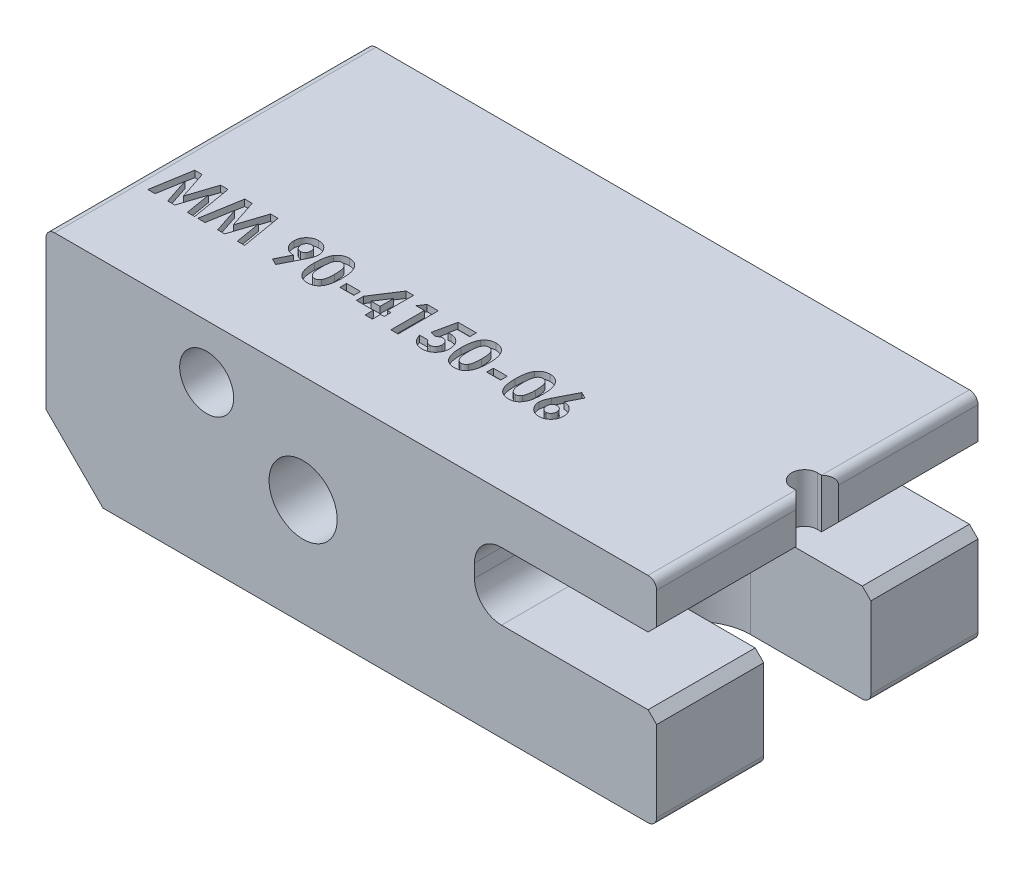
SolidWorks part; units mm, degrees
material "Acero M2"
ref_plane "Alzado" through (0, 0, 0) normal (0, 0, 1) x (1, 0, 0)
ref_plane "Planta" through (0, 0, 0) normal (0, 1, 0) x (1, 0, 0)
ref_plane "Vista lateral" through (0, 0, 0) normal (1, 0, 0) x (0, 0, -1)
sketch "Croquis1" plane through (0, 0, 0) normal (0, 1, 0) x (1, 0, 0)
  line L1 (0, 0) -> (36.195, 0)
  line L2 (0, 0) -> (0, -19.05)
  line L3 (0, -19.05) -> (36.195, -19.05)
  line L4 (36.195, 0) -> (36.195, -19.05)
  line L5 (18.0975, -19.05) -> (18.0975, 0) construction
  line L6 (0, -9.525) -> (36.195, -9.525) construction
  point P88 (18.0975, -9.525)
  dimension "D1" = 19.05
  dimension "D2" = 36.195
extrude "Saliente-Extruir1" add sketch "Croquis1" along normal blind 12.7
hole_wizard "Taladro roscado #10-321" positions "Croquis2" profile "Croquis3" tap size "#10-32" standard "Ansi Inch" end condition up to next
sketch "Croquis2" plane through (0, 0, 19.05) normal (0, 0, 1) x (1, 0, 0)
  line L0 (0, 12.7) -> (0, 0) construction
  line L1 (0, 12.7) -> (36.195, 12.7) construction
  point P0 (15.24, 6.35)
  dimension "D1" = 15.24
  dimension "D2" = 6.35
sketch "Croquis3" plane through (15.24, 6.35, 19.05) normal (1, 0, 0) x (0, -1, 0)
  line L0 (0, 0) -> (0, 19.05)
  line L1 (0, 19.05) -> (2.0193, 19.05)
  line L2 (2.0193, 19.05) -> (2.0193, 0)
  line L5 (2.0193, 0) -> (0, 0)
  line L11 (0, -6.35) -> (0, 107.95) construction
  dimension "Diámetro de perforador para roscar hasta el siguiente" = 4.0386
  dimension "Profundidad de perforador para roscar hasta el siguiente" = 19.05
cosmetic thread "Rosca de taladro1" parameters "D2"=4.826
hole_wizard "Taladros de espiga de 1/8 (0.126)1" positions "Croquis4" profile "Croquis5" hole size "1/8" standard "Ansi Inch" end condition through all
sketch "Croquis4" plane through (0, 0, 19.05) normal (0, 0, 1) x (1, 0, 0)
  line L0 (0, 12.7) -> (0, 0) construction
  line L1 (0, 12.7) -> (36.195, 12.7) construction
  point P0 (9.525, 9.525)
  dimension "D1" = 9.525
  dimension "D2" = 3.175
sketch "Croquis5" plane through (9.525, 9.525, 19.05) normal (1, 0, 0) x (0, -1, 0)
  line L0 (0, 0) -> (0, 19.05)
  line L1 (0, 19.05) -> (1.6002, 19.05)
  line L2 (1.6002, 19.05) -> (1.6002, 0)
  line L5 (1.6002, 0) -> (0, 0)
  line L11 (0, -6.35) -> (0, 107.95) construction
  dimension "Diámetro de taladro hasta el siguiente" = 3.2004
  dimension "Profundidad de taladro hasta el siguiente" = 19.05
sketch "Croquis6" plane through (0, 0, 19.05) normal (0, 0, 1) x (1, 0, 0)
  line L0 (0, 12.7) -> (36.195, 12.7) construction
  line L1 (36.195, 12.7) -> (36.195, 0) construction
  line L2 (36.195, 5.8039) -> (27.0002, 5.8039)
  line L3 (36.195, 9.7917) -> (27.0002, 9.7917)
  line L5 (25.4, 8.1915) -> (25.4, 7.4041)
  arc A0 (36.195, 5.8039) -> (36.195, 9.7917) centre (36.195, 7.7978) ccw
  arc A2 (27.0002, 9.7917) -> (25.4, 8.1915) centre (27.0002, 8.1915) ccw
  arc A3 (25.4, 7.4041) -> (27.0002, 5.8039) centre (27.0002, 7.4041) ccw
  dimension "D4" = 1.6002
  dimension "D1" = 3.9878
  dimension "D2" = 4.9022
  dimension "D3" = 10.795
extrude "Cortar-Extruir1" cut sketch "Croquis6" against normal through all
sketch "Croquis7" plane through (0, 0, 19.05) normal (0, 0, 1) x (1, 0, 0)
  line L0 (0, 3.3782) -> (3.3782, 0)
  line L1 (0, 12.7) -> (0, 0) construction
  line L2 (0, 0) -> (36.195, 0) construction
  line L3 (3.3782, 0) -> (0, 0)
  line L4 (0, 0) -> (0, 3.3782)
  line L5 (0, 12.7) -> (36.195, 12.7) construction
  dimension "D1" = 45
  dimension "D2" = 9.3218
extrude "Cortar-Extruir2" cut sketch "Croquis7" against normal through all
fillet "Redondeo1" radius 0.508 3 edges at (0, 12.7, 9.525) (36.195, 0, 9.525) (36.195, 12.7, 9.525)
chamfer "Chaflán1" distance 0.508 angle 45 2 edges at (36.195, 5.8039, 9.525) (36.195, 9.7917, 9.525)
sketch "Croquis8" plane through (0, 12.7, 0) normal (0, 1, 0) x (1, 0, 0)
  line L4 (36.195, -9.525) -> (35.433, -9.525) construction
  line L5 (36.195, 0) -> (36.195, -19.05) construction
  line L6 (36.195, -10.287) -> (35.433, -10.287)
  line L7 (36.195, -8.763) -> (35.433, -8.763)
  arc A3 (36.195, -10.287) -> (36.195, -8.763) centre (36.195, -9.525) ccw
  arc A4 (35.433, -8.763) -> (35.433, -10.287) centre (35.433, -9.525) ccw
  point P4 (35.814, -9.525)
  point P9 (34.671, -9.525)
  dimension "D1" = 1.524
  dimension "D2" = 0.762
extrude "Cortar-Extruir3" cut sketch "Croquis8" against normal through all
sketch "Croquis9" plane through (0, 0, 0) normal (0, 1, 0) x (1, 0, 0)
  line L0 (36.195, -9.525) -> (29.0576, -9.525) construction
  line L1 (36.195, -12.7) -> (29.0576, -12.7)
  line L2 (36.195, -6.35) -> (29.0576, -6.35)
  line L3 (36.195, 0) -> (36.195, -8.763) construction
  line L4 (35.687, 0) -> (0.508, 0) construction
  line L5 (36.195, 0) -> (36.195, -8.763) construction
  line L6 (29.0576, -9.525) -> (0.508, -9.525) construction
  line L7 (0.508, 0) -> (0.508, -19.05) construction
  arc A0 (36.195, -12.7) -> (36.195, -6.35) centre (36.195, -9.525) ccw
  arc A1 (29.0576, -6.35) -> (29.0576, -12.7) centre (29.0576, -9.525) ccw
  point P3 (32.6263, -9.525)
  point P8 (25.8826, -9.525)
  dimension "D1" = 10.3124
  dimension "D2" = 6.35
extrude "Cortar-Extruir4" cut sketch "Croquis9" along normal up to next
sketch "Croquis11" plane through (0, 12.7, 0) normal (0, 1, 0) x (1, 0, 0)
  line L0 (35.687, -8.763) -> (36.195, -8.255)
  line L1 (35.687, -8.763) -> (36.195, -8.763) construction
  line L2 (36.195, 0) -> (36.195, -8.763) construction
  line L3 (36.195, -8.255) -> (36.195, -8.763)
  line L4 (36.195, -8.763) -> (35.687, -8.763)
  line L5 (35.687, -10.287) -> (36.195, -10.795)
  line L6 (36.195, -10.287) -> (35.687, -10.287) construction
  line L7 (36.195, -10.287) -> (36.195, -19.05) construction
  line L8 (36.195, -10.795) -> (36.195, -10.287)
  line L9 (36.195, -10.287) -> (35.687, -10.287)
  dimension "D1" = 8.255
extrude "Cortar-Extruir5" cut sketch "Croquis11" against normal through all
sketch "Croquis12" plane through (0, 12.7, 0) normal (0, 1, 0) x (1, 0, 0)
  line L0 (0.9891, -14.0661) -> (35.2059, -14.0661) construction
  line L1 (18.0975, -14.0661) -> (18.0975, -19.05) construction
  line L2 (0.508, -19.05) -> (35.687, -19.05) construction
  text T0 "MM 90-4150-06" font "Century Gothic" height 2.3813
extrude "Cortar-Extruir6" cut sketch "Croquis12" against normal blind 0.381
